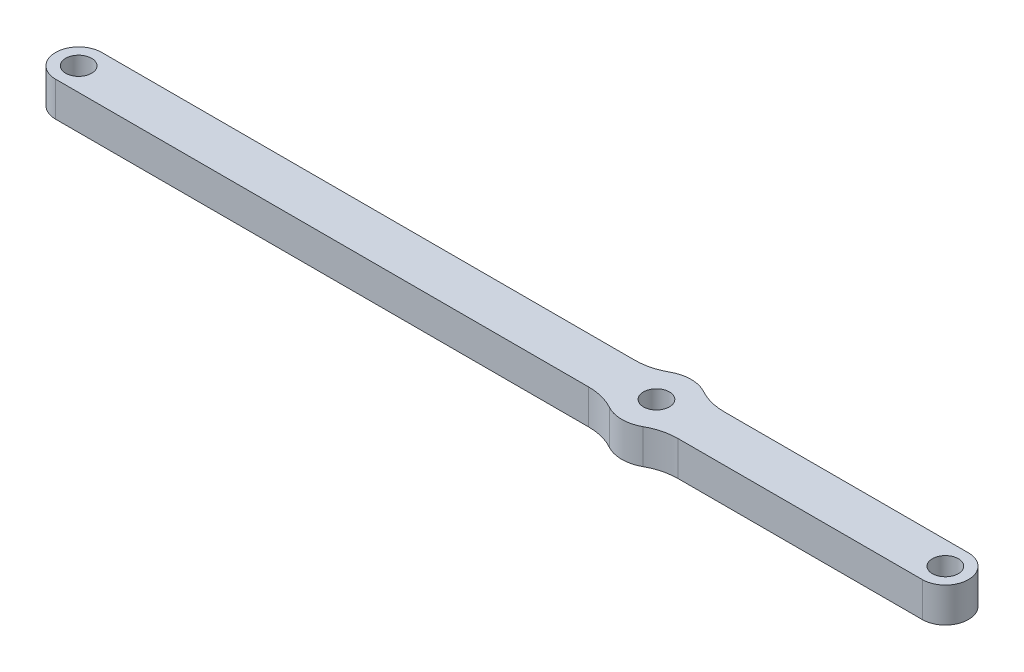
SolidWorks part; units mm, degrees
ref_plane "Front Plane" through (0, 0, 0) normal (0, 0, 1) x (1, 0, 0)
ref_plane "Top Plane" through (0, 0, 0) normal (0, 1, 0) x (1, 0, 0)
ref_plane "Right Plane" through (0, 0, 0) normal (1, 0, 0) x (0, 0, -1)
sketch "Sketch1" plane through (0, 0, 0) normal (0, 1, 0) x (1, 0, 0)
  line L0 (0, 0) -> (0, 135065.2127) construction
  line L1 (0, 0) -> (135065.2127, 0) construction
  line L2 (-100, 4) -> (-4.4721, 4)
  line L3 (4.4721, 4) -> (50, 4)
  line L4 (50, -4) -> (4.4721, -4)
  line L5 (-4.4721, -4) -> (-100, -4)
  circle A0 centre (0, 0) radius 2.25
  circle A1 centre (50, 0) radius 2.25
  circle A2 centre (-100, 0) radius 2.25
  arc A3 (-100, 4) -> (-100, -4) centre (-100, 0) ccw
  arc A4 (50, -4) -> (50, 4) centre (50, 0) ccw
  arc A5 (-4.4721, -4) -> (4.4721, -4) centre (0, 0) ccw
  arc A6 (4.4721, 4) -> (-4.4721, 4) centre (0, 0) ccw
  dimension "D1" = 4.5
  dimension "D4" = 8
  dimension "D5" = 12
  dimension "D2" = 50
  dimension "D3" = 100
extrude "Boss-Extrude1" add sketch "Sketch1" along normal blind 6
fillet "Fillet1" radius 10 4 edges at (4.4721, 3, -4) (-4.4721, 3, -4) (4.4721, 3, 4) (-4.4721, 3, 4)
